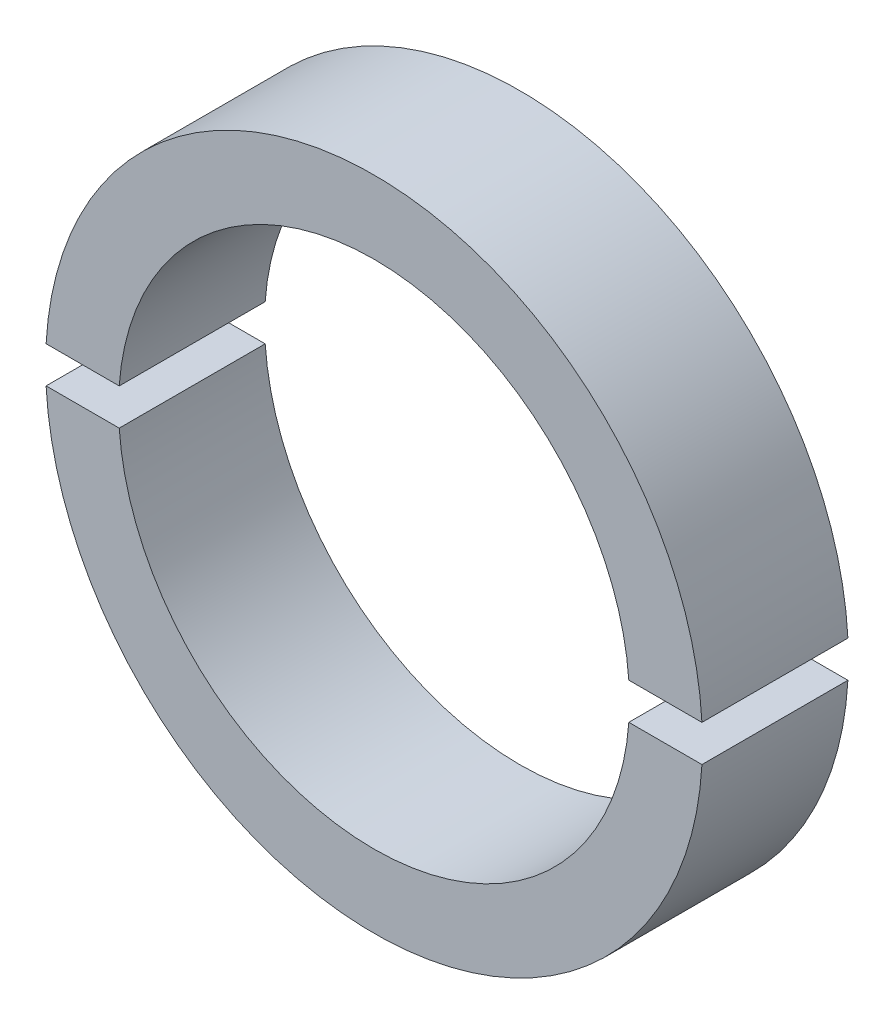
SolidWorks part; units mm, degrees
ref_plane "Vorne" through (0, 0, 0) normal (0, 0, 1) x (1, 0, 0)
ref_plane "Oben" through (0, 0, 0) normal (0, 1, 0) x (1, 0, 0)
ref_plane "Rechts" through (0, 0, 0) normal (1, 0, 0) x (0, 0, -1)
sketch "Skizze1" plane through (0, 0, 0) normal (0, 0, 1) x (1, 0, 0)
  circle A0 centre (0, 0) radius 7
  circle A1 centre (0, 0) radius 9
  dimension "D1" = 14
  dimension "D2" = 18
extrude "Aufsatz-Linear austragen1" add sketch "Skizze1" along normal blind 4
sketch "Skizze2" plane through (0, 0, 4) normal (0, 0, 1) x (1, 0, 0)
  line L1 (-13.7734, 0.5) -> (13.7734, 0.5)
  line L2 (-13.7734, 0.5) -> (-13.7734, -0.5)
  line L3 (-13.7734, -0.5) -> (13.7734, -0.5)
  line L4 (13.7734, 0.5) -> (13.7734, -0.5)
  line L5 (-13.7734, 0.5) -> (13.7734, -0.5) construction
  line L6 (-13.7734, -0.5) -> (13.7734, 0.5) construction
  point P0 (0, 0)
  dimension "D1" = 1
extrude "Schnitt-Linear austragen1" cut sketch "Skizze2" against normal blind 10
